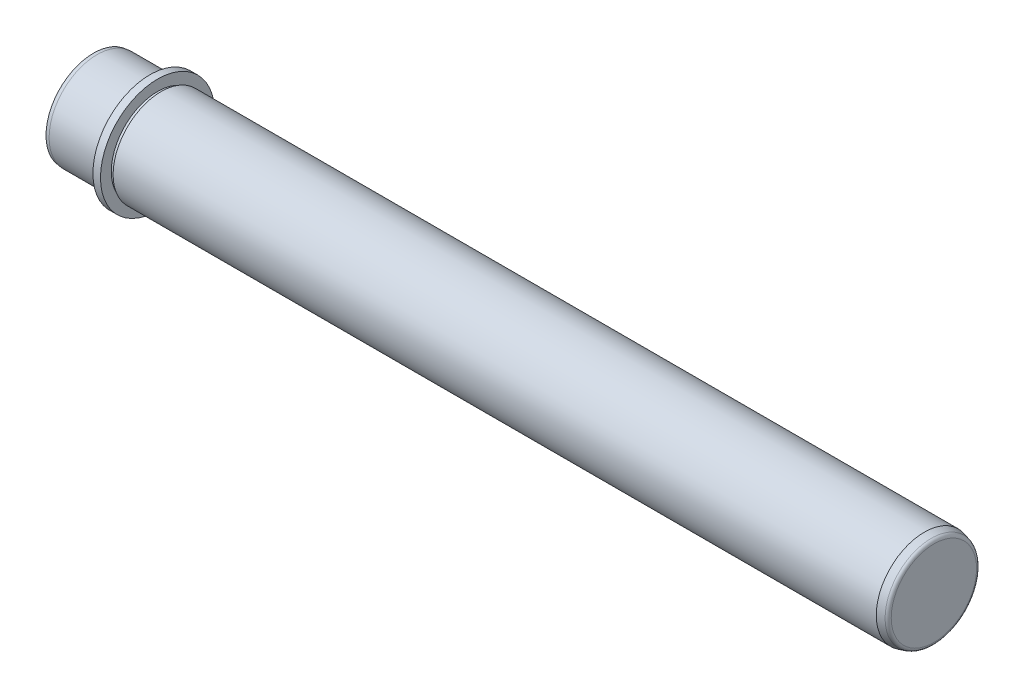
SolidWorks part; units mm, degrees
ref_plane "Front" through (0, 0, 0) normal (0, 0, 1) x (1, 0, 0)
ref_plane "Top" through (0, 0, 0) normal (0, 1, 0) x (1, 0, 0)
ref_plane "Right" through (0, 0, 0) normal (1, 0, 0) x (0, 0, -1)
sketch "Sketch1" plane through (0, 0, 0) normal (0, 0, 1) x (1, 0, 0)
  line L0 (-25.2334, 0) -> (29.1805, 0) construction
  line L1 (-22.2334, 40) -> (18.7666, 40)
  line L2 (18.7666, 40) -> (18.7666, 38.5)
  line L3 (18.7666, 38.5) -> (21.7666, 38.5)
  line L4 (21.7666, 38.5) -> (21.7666, 47.5)
  line L5 (21.7666, 47.5) -> (28.0666, 47.5)
  line L6 (28.0666, 47.5) -> (28.0666, 38.5)
  line L7 (28.0666, 38.5) -> (31.0666, 38.5)
  line L8 (31.0666, 38.5) -> (31.0666, 40)
  line L9 (31.0666, 40) -> (666.7666, 40)
  line L10 (-25.2334, 39.5784) -> (-25.2334, 0)
  line L11 (674.7666, 35.5544) -> (674.7666, 0)
  line L12 (-25.2334, 0) -> (674.7666, 0)
  line L13 (672.5431, 38.4522) -> (666.7666, 40)
  line L14 (-25.2334, 39.5784) -> (-22.2334, 40)
  line L15 (-51.273, 0) -> (217.2869, 0) construction
  arc A0 (674.7666, 35.5544) -> (672.5431, 38.4522) centre (671.7666, 35.5544) ccw
  point P20 (674.7666, 37.8564)
  dimension "D14" = 3
  dimension "D1" = 40
  dimension "D2" = 6.3
  dimension "D3" = 47.5
  dimension "D4" = 3
  dimension "D5" = 700
  dimension "D6" = 1.5
  dimension "D7" = 3
  dimension "D8" = 1.5
  dimension "D9" = 3
  dimension "D10" = 47
  dimension "D11" = 15
  dimension "D12" = 8
  dimension "D13" = 8
revolve "Base-Revolve" add sketch "Sketch1" angle 360 about L0
hole_wizard "Otwór gwintowany M12x1.51" positions "Szkic2" profile "Szkic1" tap size "M12x1.5" standard "BSI"
sketch "Szkic2" plane through (-25.2334, 0, 0) normal (-1, 0, 0) x (0, 0, 1)
  point P0 (0, 0)
sketch "Szkic1" plane through (-25.2334, 0, 0) normal (0, 1, 0) x (0, 0, 1)
  line L0 (0, 0) -> (0, 34.6545)
  line L1 (0, 34.6545) -> (5.25, 31.5)
  line L2 (5.25, 31.5) -> (5.25, 0.775)
  line L3 (5.25, 0.775) -> (6.025, 0)
  line L5 (6.025, 0) -> (0, 0)
  line L6 (-5.25, 0.775) -> (-6.025, 0) construction
  line L10 (0, 34.6545) -> (-5.25, 31.5) construction
  line L11 (0, -6.35) -> (0, 107.95) construction
  dimension "Średnica wiertła gwintu" = 10.5
  dimension "Głębokość otworu gwintowanego" = 31.5
  dimension "Średnica zewnętrznego pogłębienia stożkowego" = 12.05
  dimension "Kąt zewnętrznego pogłębienia stożkowego" = 90
  dimension "Kąt wiertła" = 118
cosmetic thread "Gwint otworu1" parameters "D1"=24, "D2"=12
